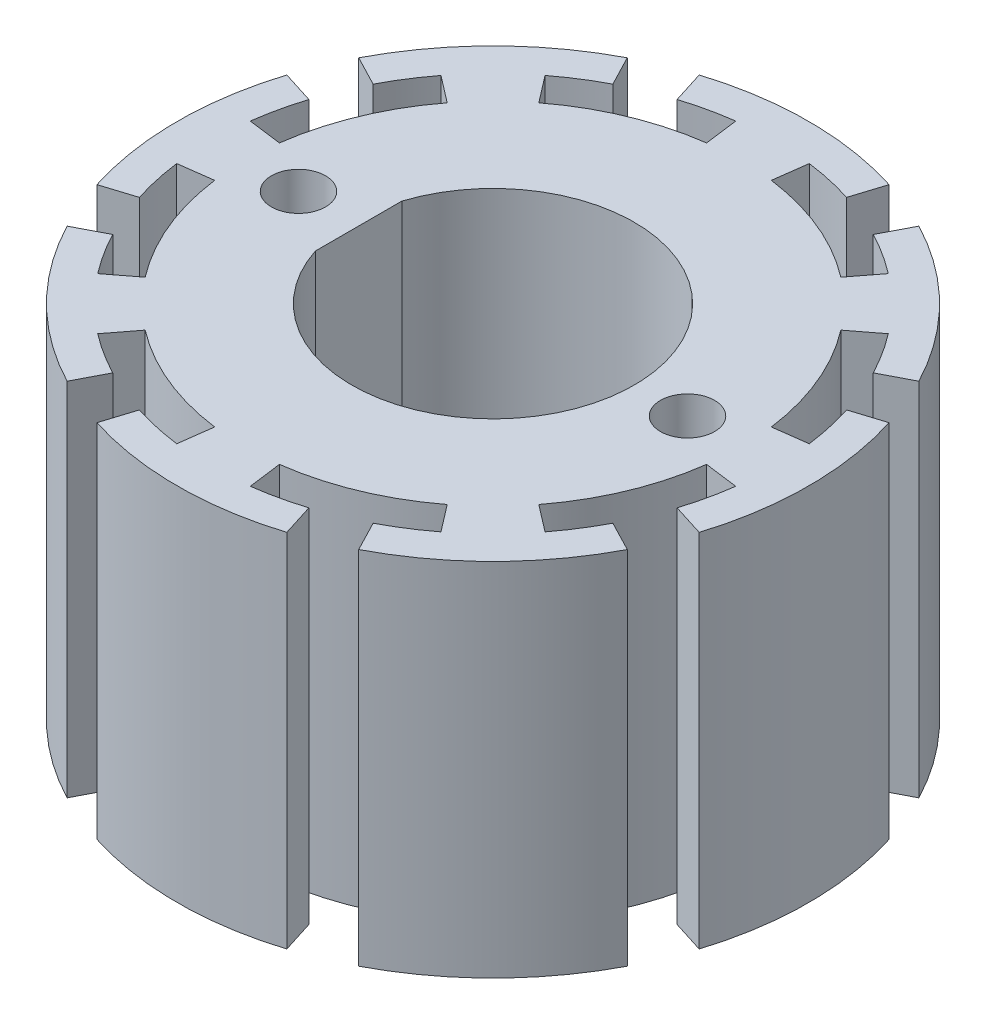
SolidWorks part; units mm, degrees
material "ABS"
ref_plane "Front Plane" through (0, 0, 0) normal (1, 0, 0) x (0, 1, 0)
ref_plane "Top Plane" through (0, 0, 0) normal (0, 0, 1) x (0, 1, 0)
ref_plane "Right Plane" through (0, 0, 0) normal (0, 1, 0) x (-1, 0, 0)
sketch "Sketch1" plane through (0, 0, 0) normal (1, 0, 0) x (0, 1, 0)
  line L0 (0, 0) -> (-37.386, 0) construction
  line L1 (0, 7.9502) -> (-20.32, 7.9502)
  line L2 (-20.32, 7.9502) -> (-20.32, 17.78)
  line L3 (-20.32, 17.78) -> (0, 17.78)
  line L4 (0, 17.78) -> (0, 14.605)
  line L5 (0, 14.605) -> (-5.08, 14.605)
  line L6 (-5.08, 14.605) -> (-5.08, 14.3002)
  line L7 (-5.08, 14.3002) -> (0, 14.3002)
  line L8 (0, 14.3002) -> (0, 7.9502)
  line L9 (0, 14.605) -> (0, 14.3002)
  line L10 (0, 14.605) -> (0, 14.3002)
  dimension "D1" = 7.9502
  dimension "D2" = 6.35
  dimension "D3" = 17.78
  dimension "D4" = 20.32
  dimension "D5" = 3.175
  dimension "D6" = 5.08
revolve "Revolve1" add sketch "Sketch1" angle 360 about L0
sketch "Sketch2" plane through (0, 0, 0) normal (0, 1, 0) x (-1, 0, 0)
  line L0 (0, 0) -> (16.9571, 5.3465) construction
  line L1 (0, 0) -> (15.7711, 8.2099) construction
  line L2 (0, 0) -> (12.5724, 12.5724) construction
  line L3 (0, 0) -> (17.78, 0) construction
  line L4 (15.7711, 8.2099) -> (14.0813, 7.3303)
  line L5 (0, 0) -> (12.5945, 9.6641) construction
  line L6 (0, 0) -> (15.7392, 2.0721) construction
  line L7 (16.9571, 5.3465) -> (15.1403, 4.7737)
  line L8 (12.5945, 9.6641) -> (11.0831, 8.5044)
  line L9 (15.7392, 2.0721) -> (13.8505, 1.8235)
  circle A0 centre (0, 0) radius 17.78 construction
  circle A1 centre (0, 0) radius 15.875 construction
  circle A2 centre (0, 0) radius 17.78 construction
  circle A3 centre (0, 0) radius 13.97 construction
  arc A4 (14.0813, 7.3303) -> (12.5945, 9.6641) centre (0, 0) ccw
  arc A5 (15.1403, 4.7737) -> (15.7392, 2.0721) centre (0, 0) cw
  arc A6 (11.0831, 8.5044) -> (13.8505, 1.8235) centre (0, 0) cw
  arc A7 (15.7711, 8.2099) -> (16.9571, 5.3465) centre (0, 0) cw
  dimension "D6" = 35.56
  dimension "D7" = 31.75
  dimension "D8" = 27.94
  dimension "D1" = 10
  dimension "D2" = 17.5
  dimension "D3" = 17.5
  dimension "D4" = 10
  dimension "D5" = 10
extrude "Cut-Extrude1" cut sketch "Sketch2" against normal through all contours A7 L4 A4 L8 A6 L9 A5 L7
sketch "Sketch4" plane through (0, 0, 0) normal (0, 0, 1) x (0, 1, 0)
  line L0 (0, 0) -> (-20.32, 0) construction
  line L2 (-20.32, 17.78) -> (-20.32, -17.78) construction
pattern_circular "CirPattern1" count 8 over 360 about axis through (0, 0, 0) along (0, 1, 0) of "Cut-Extrude1"
sketch "Sketch5" plane through (0, 0, 0) normal (0, 1, 0) x (1, 0, 0)
  line L0 (-7.5692, -2.4316) -> (-7.5692, 2.4316)
  circle A0 centre (0, 0) radius 7.9502 construction
  arc A1 (-7.5692, 2.4316) -> (-7.5692, -2.4316) centre (0, 0) cw
  arc A2 (-7.5692, 2.4316) -> (-7.5692, -2.4316) centre (0, 0) ccw
  dimension "D1" = 7.5692
extrude "Boss-Extrude1" add sketch "Sketch5" against normal up to surface (20.32 mm away) contours L0 A2 up to face at (0, -20.32, 7.9502)
sketch "Sketch6" plane through (0, 0, 0) normal (0, 1, 0) x (-1, 0, 0)
  circle A0 centre (0, 0) radius 6.9342
  circle A1 centre (0, 0) radius 12.2
  dimension "D1" = 13.8684
  dimension "D2" = 24.4
extrude "40 tooth gear" [suppressed] add sketch "Sketch6" along normal blind 6.5
sketch "Sketch7" [suppressed] plane through (0, 6.5, 0) normal (0, 1, 0) x (-1, 0, 0)
  circle A0 centre (0, 0) radius 6.9342
  circle A1 centre (0, 0) radius 13.2
  circle A2 centre (0, 0) radius 6.9342 construction
  dimension "D1" = 26.4
extrude "Boss-Extrude3" [suppressed] add sketch "Sketch7" along normal blind 1.016
sketch "Sketch8" plane through (0, 0, 0) normal (0, 1, 0) x (-1, 0, 0)
  line L0 (10.9537, 0) -> (-10.9537, 0) construction
  circle A0 centre (-10.9537, 0) radius 1.524
  circle A1 centre (10.9537, 0) radius 1.524
  point P5 (0, 0)
  dimension "D1" = 3.048
  dimension "D2" = 21.9075
sketch "Sketch11" plane through (0, -20.32, 0) normal (0, 1, 0) x (-1, 0, 0)
  circle A0 centre (-10.9537, 0) radius 2.921
  circle A1 centre (10.9537, 0) radius 2.921
  dimension "D1" = 5.842
extrude "Cut-Extrude2" cut sketch "Sketch8" against normal through all
extrude "Cut-Extrude3" [suppressed] cut sketch "Sketch11" along normal blind 12.7
equation "\"D1@Sketch5\"=0.313-0.015"
equation "\"D1@40 tooth gear\" = 6.5mm"
equation "\"D2@Sketch6\"=24.4mm"
equation "\"D1@Sketch7\"=26.4mm"
equation "\"D1@Sketch6\"=2*(0.313-0.04)"
